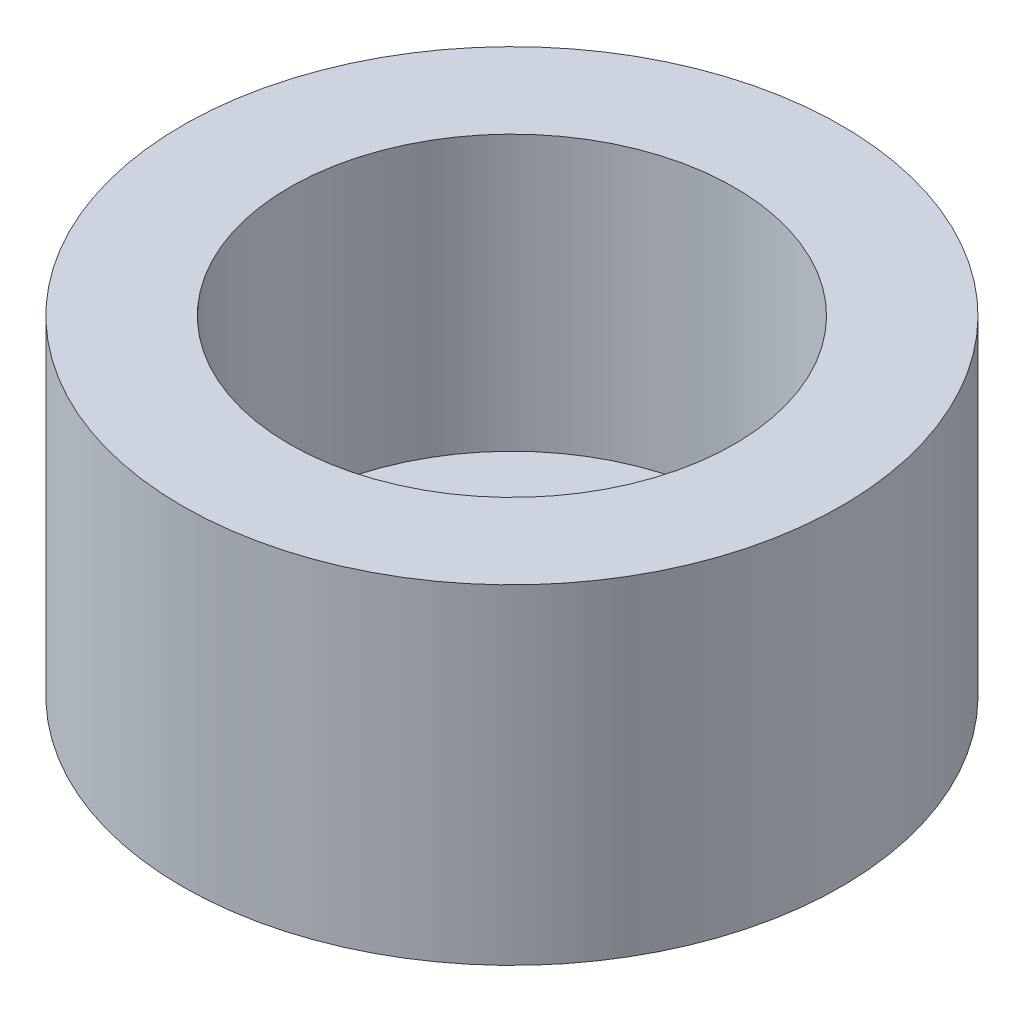
SolidWorks part; units mm, degrees
ref_plane "Ebene vorne" through (0, 0, 0) normal (0, 0, 1) x (1, 0, 0)
ref_plane "Ebene oben" through (0, 0, 0) normal (0, 1, 0) x (1, 0, 0)
ref_plane "Ebene rechts" through (0, 0, 0) normal (1, 0, 0) x (0, 0, -1)
sketch "Skizze1" plane through (0, 0, 0) normal (0, 1, 0) x (1, 0, 0)
  circle A0 centre (0, 0) radius 6
  circle A1 centre (0, 0) radius 1.75
  dimension "D1" = 12
  dimension "D2" = 3.5
extrude "Aufsatz-Linear austragen1" add sketch "Skizze1" along normal blind 1
sketch "Skizze4" plane through (0, 1, 0) normal (0, 1, 0) x (1, 0, 0)
  circle A0 centre (0, 0) radius 6
  circle A1 centre (0, 0) radius 4.05
  dimension "D1" = 8.1
  dimension "D2" = 12
extrude "Aufsatz-Linear austragen2" add sketch "Skizze4" along normal blind 5
